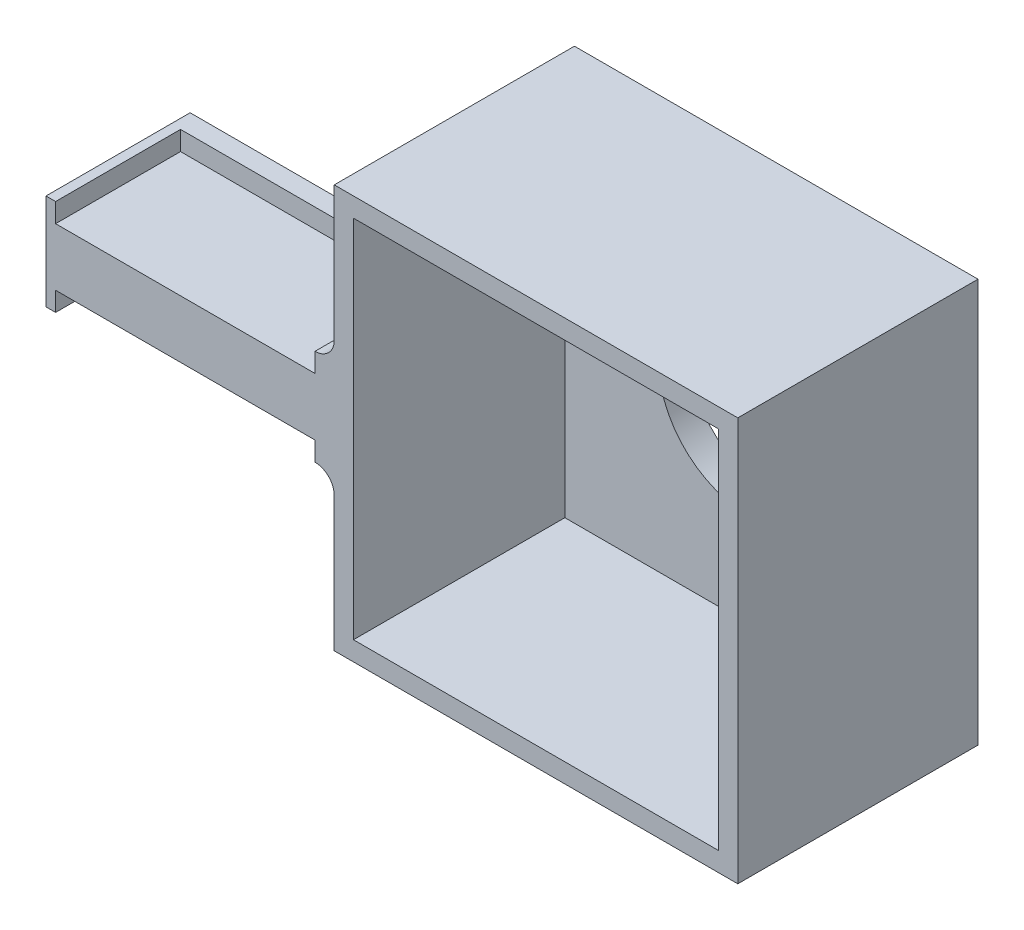
SolidWorks part; units mm, degrees
ref_plane "정면" through (0, 0, 0) normal (0, 0, 1) x (1, 0, 0)
ref_plane "윗면" through (0, 0, 0) normal (0, 1, 0) x (1, 0, 0)
ref_plane "우측면" through (0, 0, 0) normal (1, 0, 0) x (0, 0, -1)
sketch "스케치1" plane through (0, 0, 0) normal (0, 0, 1) x (1, 0, 0)
  line L1 (0, 0) -> (42, 0)
  line L2 (0, 0) -> (0, -42)
  line L3 (0, -42) -> (42, -42)
  line L4 (42, 0) -> (42, -42)
  dimension "D1" = 42
  dimension "D2" = 42
extrude "보스-돌출1" add sketch "스케치1" along normal blind 25
sketch "스케치2" plane through (0, 0, 25) normal (0, 0, 1) x (1, 0, 0)
  line L0 (42, 0) -> (0, 0) construction
  line L1 (2, -2) -> (40, -2)
  line L2 (2, -2) -> (2, -40)
  line L3 (2, -40) -> (40, -40)
  line L4 (40, -2) -> (40, -40)
  line L5 (0, 0) -> (0, -42) construction
  dimension "D1" = 38
  dimension "D2" = 38
  dimension "D3" = 2
  dimension "D4" = 2
extrude "컷-돌출1" cut sketch "스케치2" against normal blind 22
sketch "스케치3" plane through (0, 0, 0) normal (0, 0, -1) x (-1, 0, 0)
  line L0 (-42, 0) -> (0, 0) construction
  line L1 (0, 0) -> (0, -42) construction
  circle A0 centre (-21, -21) radius 9.25
  dimension "D1" = 21
  dimension "D2" = 18.5
  dimension "D3" = 21
extrude "컷-돌출2" cut sketch "스케치3" against normal through all
sketch "스케치4" plane through (0, 0, 0) normal (-1, 0, 0) x (0, 0, 1)
  line L0 (25, 0) -> (25, -42) construction
  line L1 (10, -26) -> (25, -26)
  line L2 (10, -26) -> (10, -16)
  line L3 (10, -16) -> (25, -16)
  line L4 (25, -26) -> (25, -16)
  line L5 (25, 0) -> (0, 0) construction
  dimension "D1" = 10
  dimension "D2" = 16
  dimension "D3" = 15
extrude "보스-돌출2" add sketch "스케치4" along normal blind 30
sketch "스케치5" plane through (0, -26, 0) normal (0, -1, 0) x (1, 0, 0)
  line L0 (-30, 25) -> (0, 25) construction
  line L1 (-2, 13) -> (-29, 13)
  line L2 (-2, 13) -> (-2, 25)
  line L3 (-2, 25) -> (-29, 25)
  line L4 (-29, 13) -> (-29, 25)
  line L5 (0, 10) -> (0, 25) construction
  dimension "D1" = 27
  dimension "D2" = 2
  dimension "D3" = 12
extrude "컷-돌출3" cut sketch "스케치5" against normal blind 2
sketch "스케치6" plane through (0, -16, 0) normal (0, 1, 0) x (1, 0, 0)
  line L0 (-30, -25) -> (0, -25) construction
  line L1 (-29, -12) -> (-2, -12)
  line L2 (-29, -12) -> (-29, -25)
  line L3 (-29, -25) -> (-2, -25)
  line L4 (-2, -12) -> (-2, -25)
  line L5 (0, -25) -> (0, -10) construction
  dimension "D1" = 27
  dimension "D2" = 2
  dimension "D3" = 13
extrude "컷-돌출4" cut sketch "스케치6" against normal blind 2
fillet "필렛1" radius 2 2 edges at (0, -26, 17.5) (0, -16, 17.5)
